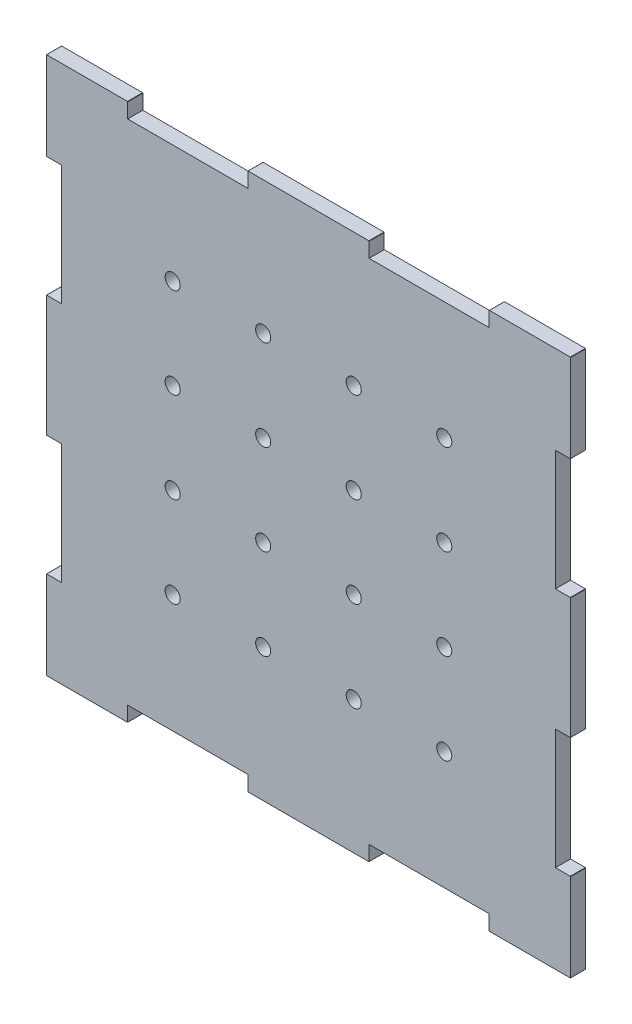
SolidWorks part; units mm, degrees
ref_plane "Front Plane" through (0, 0, 0) normal (0, 0, 1) x (1, 0, 0)
ref_plane "Top Plane" through (0, 0, 0) normal (0, 1, 0) x (1, 0, 0)
ref_plane "Right Plane" through (0, 0, 0) normal (1, 0, 0) x (0, 0, -1)
sketch "Model" plane through (0, 0, 0) normal (0, 0, 1) x (1, 0, 0)
  line L0 (-59.94, -89.08) -> (-59.93, -89.07)
  line L1 (-59.93, -89.07) -> (-59.92, -89.05)
  line L2 (-59.92, -89.05) -> (-59.91, -89.04)
  line L3 (-59.91, -89.04) -> (-59.9, -89.02)
  line L4 (-59.9, -89.02) -> (-59.9, -84.1)
  line L5 (-59.9, -84.1) -> (-20.1, -84.1)
  line L6 (-20.1, -84.1) -> (-20.1, -89.02)
  line L7 (-20.1, -89.02) -> (-20.08, -89.06)
  line L8 (-20.08, -89.06) -> (-20.07, -89.07)
  line L9 (-20.07, -89.07) -> (-20.05, -89.08)
  line L10 (-20.05, -89.08) -> (-20.04, -89.09)
  line L11 (-20.04, -89.09) -> (-20.02, -89.1)
  line L12 (-20.02, -89.1) -> (20.02, -89.1)
  line L13 (20.02, -89.1) -> (20.06, -89.08)
  line L14 (20.06, -89.08) -> (20.07, -89.07)
  line L15 (20.07, -89.07) -> (20.08, -89.05)
  line L16 (20.08, -89.05) -> (20.09, -89.04)
  line L17 (20.09, -89.04) -> (20.1, -89.02)
  line L18 (20.1, -89.02) -> (20.1, -84.1)
  line L19 (20.1, -84.1) -> (59.9, -84.1)
  line L20 (59.9, -84.1) -> (59.9, -89.02)
  line L21 (59.9, -89.02) -> (59.92, -89.06)
  line L22 (59.92, -89.06) -> (59.93, -89.07)
  line L23 (59.93, -89.07) -> (59.95, -89.08)
  line L24 (59.95, -89.08) -> (59.96, -89.09)
  line L25 (59.96, -89.09) -> (59.98, -89.1)
  line L26 (59.98, -89.1) -> (86.77, -89.1)
  line L27 (86.77, -89.1) -> (86.81, -89.08)
  line L28 (86.81, -89.08) -> (86.82, -89.07)
  line L29 (86.82, -89.07) -> (86.83, -89.05)
  line L30 (86.83, -89.05) -> (86.84, -89.04)
  line L31 (86.84, -89.04) -> (86.85, -89.02)
  line L32 (86.85, -89.02) -> (86.85, -59.98)
  line L33 (86.85, -59.98) -> (86.83, -59.94)
  line L34 (86.83, -59.94) -> (86.82, -59.93)
  line L35 (86.82, -59.93) -> (86.8, -59.92)
  line L36 (86.8, -59.92) -> (86.79, -59.91)
  line L37 (86.79, -59.91) -> (86.77, -59.9)
  line L38 (86.77, -59.9) -> (81.85, -59.9)
  line L39 (81.85, -59.9) -> (81.85, -20.1)
  line L40 (81.85, -20.1) -> (86.77, -20.1)
  line L41 (86.77, -20.1) -> (86.81, -20.08)
  line L42 (86.81, -20.08) -> (86.82, -20.07)
  line L43 (86.82, -20.07) -> (86.83, -20.05)
  line L44 (86.83, -20.05) -> (86.84, -20.04)
  line L45 (86.84, -20.04) -> (86.85, -20.02)
  line L46 (86.85, -20.02) -> (86.85, 20.02)
  line L47 (86.85, 20.02) -> (86.83, 20.06)
  line L48 (86.83, 20.06) -> (86.82, 20.07)
  line L49 (86.82, 20.07) -> (86.8, 20.08)
  line L50 (86.8, 20.08) -> (86.79, 20.09)
  line L51 (86.79, 20.09) -> (86.77, 20.1)
  line L52 (86.77, 20.1) -> (81.85, 20.1)
  line L53 (81.85, 20.1) -> (81.85, 59.9)
  line L54 (81.85, 59.9) -> (86.77, 59.9)
  line L55 (86.77, 59.9) -> (86.81, 59.92)
  line L56 (86.81, 59.92) -> (86.82, 59.93)
  line L57 (86.82, 59.93) -> (86.83, 59.95)
  line L58 (86.83, 59.95) -> (86.84, 59.96)
  line L59 (86.84, 59.96) -> (86.85, 59.98)
  line L60 (86.85, 59.98) -> (86.85, 89.02)
  line L61 (86.85, 89.02) -> (86.83, 89.06)
  line L62 (86.83, 89.06) -> (86.82, 89.07)
  line L63 (86.82, 89.07) -> (86.8, 89.08)
  line L64 (86.8, 89.08) -> (86.79, 89.09)
  line L65 (86.79, 89.09) -> (86.77, 89.1)
  line L66 (86.77, 89.1) -> (59.98, 89.1)
  line L67 (59.98, 89.1) -> (59.94, 89.08)
  line L68 (59.94, 89.08) -> (59.93, 89.07)
  line L69 (59.93, 89.07) -> (59.92, 89.05)
  line L70 (59.92, 89.05) -> (59.91, 89.04)
  line L71 (59.91, 89.04) -> (59.9, 89.02)
  line L72 (59.9, 89.02) -> (59.9, 84.1)
  line L73 (59.9, 84.1) -> (20.1, 84.1)
  line L74 (20.1, 84.1) -> (20.1, 89.02)
  line L75 (20.1, 89.02) -> (20.08, 89.06)
  line L76 (20.08, 89.06) -> (20.07, 89.07)
  line L77 (20.07, 89.07) -> (20.05, 89.08)
  line L78 (20.05, 89.08) -> (20.04, 89.09)
  line L79 (20.04, 89.09) -> (20.02, 89.1)
  line L80 (20.02, 89.1) -> (-20.02, 89.1)
  line L81 (-20.02, 89.1) -> (-20.06, 89.08)
  line L82 (-20.06, 89.08) -> (-20.07, 89.07)
  line L83 (-20.07, 89.07) -> (-20.08, 89.05)
  line L84 (-20.08, 89.05) -> (-20.09, 89.04)
  line L85 (-20.09, 89.04) -> (-20.1, 89.02)
  line L86 (-20.1, 89.02) -> (-20.1, 84.1)
  line L87 (-20.1, 84.1) -> (-59.9, 84.1)
  line L88 (-59.9, 84.1) -> (-59.9, 89.02)
  line L89 (-59.9, 89.02) -> (-59.92, 89.06)
  line L90 (-59.92, 89.06) -> (-59.93, 89.07)
  line L91 (-59.93, 89.07) -> (-59.95, 89.08)
  line L92 (-59.95, 89.08) -> (-59.96, 89.09)
  line L93 (-59.96, 89.09) -> (-59.98, 89.1)
  line L94 (-59.98, 89.1) -> (-86.77, 89.1)
  line L95 (-86.77, 89.1) -> (-86.81, 89.08)
  line L96 (-86.81, 89.08) -> (-86.82, 89.07)
  line L97 (-86.82, 89.07) -> (-86.83, 89.05)
  line L98 (-86.83, 89.05) -> (-86.84, 89.04)
  line L99 (-86.84, 89.04) -> (-86.85, 89.02)
  line L100 (-86.85, 89.02) -> (-86.85, 59.98)
  line L101 (-86.85, 59.98) -> (-86.83, 59.94)
  line L102 (-86.83, 59.94) -> (-86.82, 59.93)
  line L103 (-86.82, 59.93) -> (-86.8, 59.92)
  line L104 (-86.8, 59.92) -> (-86.79, 59.91)
  line L105 (-86.79, 59.91) -> (-86.77, 59.9)
  line L106 (-86.77, 59.9) -> (-81.85, 59.9)
  line L107 (-81.85, 59.9) -> (-81.85, 20.1)
  line L108 (-81.85, 20.1) -> (-86.77, 20.1)
  line L109 (-86.77, 20.1) -> (-86.81, 20.08)
  line L110 (-86.81, 20.08) -> (-86.82, 20.07)
  line L111 (-86.82, 20.07) -> (-86.83, 20.05)
  line L112 (-86.83, 20.05) -> (-86.84, 20.04)
  line L113 (-86.84, 20.04) -> (-86.85, 20.02)
  line L114 (-86.85, 20.02) -> (-86.85, -20.02)
  line L115 (-86.85, -20.02) -> (-86.83, -20.06)
  line L116 (-86.83, -20.06) -> (-86.82, -20.07)
  line L117 (-86.82, -20.07) -> (-86.8, -20.08)
  line L118 (-86.8, -20.08) -> (-86.79, -20.09)
  line L119 (-86.79, -20.09) -> (-86.77, -20.1)
  line L120 (-86.77, -20.1) -> (-81.85, -20.1)
  line L121 (-81.85, -20.1) -> (-81.85, -59.9)
  line L122 (-81.85, -59.9) -> (-86.77, -59.9)
  line L123 (-86.77, -59.9) -> (-86.81, -59.92)
  line L124 (-86.81, -59.92) -> (-86.82, -59.93)
  line L125 (-86.82, -59.93) -> (-86.83, -59.95)
  line L126 (-86.83, -59.95) -> (-86.84, -59.96)
  line L127 (-86.84, -59.96) -> (-86.85, -59.98)
  line L128 (-86.85, -59.98) -> (-86.85, -89.02)
  line L129 (-86.85, -89.02) -> (-86.83, -89.06)
  line L130 (-86.83, -89.06) -> (-86.82, -89.07)
  line L131 (-86.82, -89.07) -> (-86.8, -89.08)
  line L132 (-86.8, -89.08) -> (-86.79, -89.09)
  line L133 (-86.79, -89.09) -> (-86.77, -89.1)
  line L134 (-86.77, -89.1) -> (-59.98, -89.1)
  line L135 (-59.98, -89.1) -> (-59.94, -89.08)
extrude "Boss-Extrude1" add sketch "Model" along normal blind 5
sketch "Sketch2" plane through (0, 0, 5) normal (0, 0, 1) x (1, 0, 0)
  line L5 (45, -45) -> (-45, 45) construction
  line L6 (45, 45) -> (-45, -45) construction
  circle A0 centre (-45, 45) radius 2.5
  circle A1 centre (-15, 45) radius 2.5
  circle A2 centre (15, 45) radius 2.5
  circle A3 centre (45, 45) radius 2.5
  circle A4 centre (-15, 15) radius 2.5
  circle A5 centre (15, 15) radius 2.5
  circle A6 centre (45, 15) radius 2.5
  circle A7 centre (-15, -15) radius 2.5
  circle A8 centre (15, -15) radius 2.5
  circle A9 centre (45, -15) radius 2.5
  circle A10 centre (-15, -45) radius 2.5
  circle A11 centre (15, -45) radius 2.5
  circle A12 centre (45, -45) radius 2.5
  circle A13 centre (-45, 15) radius 2.5
  circle A14 centre (-45, -15) radius 2.5
  circle A15 centre (-45, -45) radius 2.5
  point P0 (0, 0)
  dimension "D3" = 5
  dimension "D1" = 90
  dimension "D2" = 90
  dimension "D4" = 4
  dimension "D5" = 4
extrude "Cut-Extrude1" cut sketch "Sketch2" against normal through all
